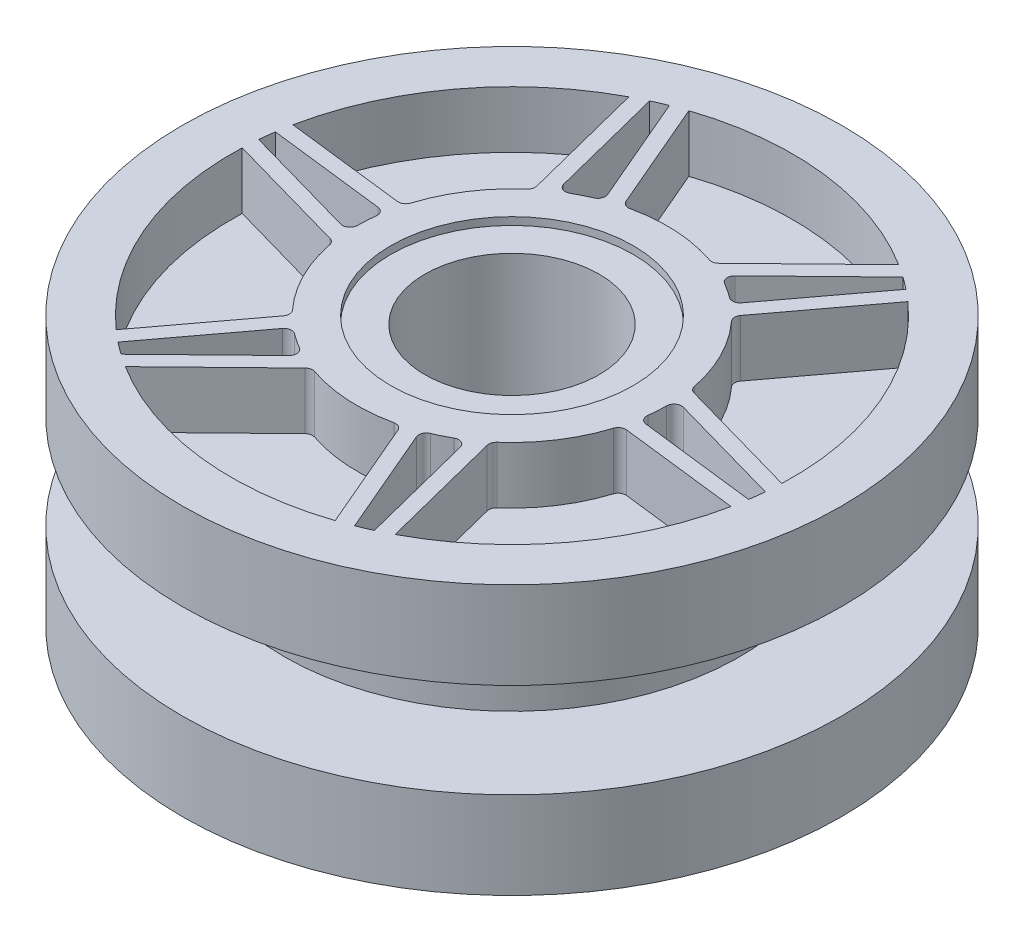
SolidWorks part; units mm, degrees
material "ABS"
ref_plane "Front Plane" through (0, 0, 0) normal (0, 0, 1) x (1, 0, 0)
ref_plane "Top Plane" through (0, 0, 0) normal (0, 1, 0) x (1, 0, 0)
ref_plane "Right Plane" through (0, 0, 0) normal (1, 0, 0) x (0, 0, -1)
sketch "Sketch1" plane through (0, 0, 0) normal (0, 1, 0) x (1, 0, 0)
  circle A0 centre (0, 0) radius 8.7
  dimension "D1" = 17.4
extrude "Boss-Extrude1" add sketch "Sketch1" along normal blind 2.3
sketch "Sketch2" plane through (0, 2.3, 0) normal (0, 1, 0) x (1, 0, 0)
  circle A0 centre (0, 0) radius 6
  dimension "D1" = 12
extrude "Boss-Extrude2" add sketch "Sketch2" along normal blind 1.25
sketch "Sketch3" plane through (0, 0, 0) normal (0, -1, 0) x (1, 0, 0)
  circle A0 centre (0, 0) radius 7.4
  circle A1 centre (0, 0) radius 8.7 construction
  circle A2 centre (0, 0) radius 4.1
  circle A3 centre (0, 0) radius 3.2
  point P0 (0.8161, 6.6342)
  point P7 (0, 0)
  point P9 (0, 0)
  point P10 (2.2548, 4.8625)
  point P20 (-1.0036, 3.901)
  point P21 (0.5022, 4.0985)
  point P22 (-0.1214, 7.3914)
  point P23 (-0.2615, 4.0691)
  point P24 (0.58, 4.0917)
  point P25 (0, 0)
  dimension "D1" = 1.3
  dimension "D2" = 0.9
  dimension "D3" = 8.2
extrude "Cut-Extrude2" cut sketch "Sketch3" against normal blind 1.5 contours A3 | A0 A2
sketch "Sketch6" plane through (0, 1.5, 0) normal (0, -1, 0) x (1, 0, 0)
  circle A1 centre (0, 0) radius 3.2
  circle A2 centre (0, 0) radius 3.2
  dimension "D1" = 0
extrude "Boss-Extrude3" add sketch "Sketch6" along normal blind 1.3
sketch "Sketch7" plane through (0, 0.2, 0) normal (0, -1, 0) x (1, 0, 0)
  circle A0 centre (0, 0) radius 2.3
  dimension "D1" = 4.6
extrude "Cut-Extrude3" cut sketch "Sketch7" against normal through all
ref_plane "Plane1" through (0, 3.55, 0) normal (0, 1, 0) x (1, 0, 0)
mirror "Mirror4" about plane through (0, 3.55, 0) normal (0, 1, 0) of bodies 106
sketch "Sketch9" plane through (0, 1.5, 0) normal (0, -1, 0) x (1, 0, 0)
  circle A0 centre (0, -5.558) radius 0.75
  circle A1 centre (0, 0) radius 7.4 construction
  dimension "D1" = 1.5
  dimension "D2" = 5.558
extrude "Cut-Extrude4" cut sketch "Sketch9" against normal blind 0.2
pattern_circular "CirPattern1" count 6 over 360 about axis through (0, 0, 0) along (0, 1, 0) of "Cut-Extrude4"
sketch "Sketch10" plane through (0, 7.1, 0) normal (0, 1, 0) x (1, 0, 0)
  line L0 (7.321, -1.0782) -> (4.0422, -0.6857)
  line L1 (7.252, -1.4728) -> (3.9557, -1.0782)
  line L2 (7.3683, -0.6838) -> (4.0929, 0.2416)
  line L3 (7.3949, -0.2757) -> (4.0447, 0.6709)
  line L4 (0, 0) -> (4.0447, 0.6709)
  line L5 (0, 0) -> (3.9557, -1.0782) construction
  circle A0 centre (0, 0) radius 4.1 construction
  circle A1 centre (0, 0) radius 8.7
  circle A2 centre (0, 0) radius 8.7 construction
  circle A3 centre (0, 0) radius 4.1 construction
  circle A4 centre (0, 0) radius 7.4 construction
  circle A5 centre (0, 0) radius 7.4 construction
  arc A6 (7.321, -1.0782) -> (7.252, -1.4728) centre (0, 0) cw
  arc A7 (4.0422, -0.6857) -> (3.9557, -1.0782) centre (0, 0) cw
  arc A8 (7.3949, -0.2757) -> (7.3683, -0.6838) centre (0, 0) cw
  arc A9 (4.0447, 0.6709) -> (4.0929, 0.2416) centre (0, 0) cw
  point P18 (0, 0)
  point P19 (0, 0)
  point P23 (0, 0)
  point P24 (0, 0)
  point P25 (0, 0)
  dimension "D2" = 0.4
  dimension "D3" = 0.4
  dimension "D1" = 0
extrude "Boss-Extrude4" add sketch "Sketch10" against normal up to surface (1.5 mm away) contours A9 L2 A8 L3 | A7 L1 A6 L0 up to face at (0, 5.6, -4.1)
pattern_circular "CirPattern2" count 6 over 360 about axis through (0, 0, 0) along (0, 1, 0) of "Boss-Extrude4"
fillet "Fillet2" radius 0.2 24 edges at (1.8372, 6.35, -3.6653) (4.0447, 6.35, -0.6709) (4.0422, 6.35, 0.6857) (2.615, 6.35, -3.1578) (2.9116, 6.35, -2.8866) (4.0929, 6.35, -0.2416) (-2.2557, 6.35, -3.4237) (-1.4273, 6.35, -3.8436) (3.9557, 6.35, 1.0782) (2.6033, 6.35, 3.1674) (2.2557, 6.35, 3.4237) (1.4273, 6.35, 3.8436) (1.0441, 6.35, 3.9648) (-1.4414, 6.35, 3.8383) (-1.8372, 6.35, 3.6653) (-2.615, 6.35, 3.1578) (-2.9116, 6.35, 2.8866) (-4.0447, 6.35, 0.6709) (-4.0929, 6.35, 0.2416) (-4.0422, 6.35, -0.6857) (-3.9557, 6.35, -1.0782) (-2.6033, 6.35, -3.1674) (-1.0441, 6.35, -3.9648) (1.4414, 6.35, -3.8383)
